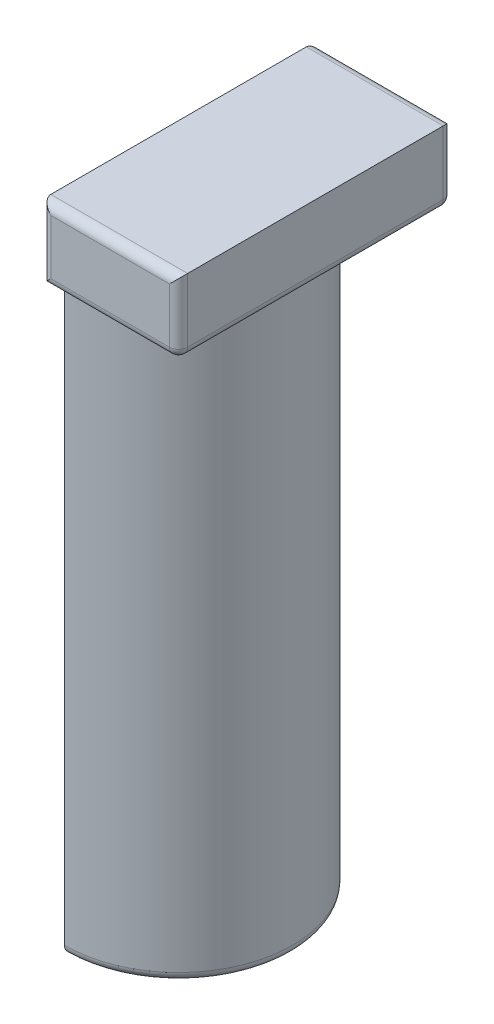
SolidWorks part; units mm, degrees
ref_plane "前视基准面" through (0, 0, 0) normal (0, 0, 1) x (1, 0, 0)
ref_plane "上视基准面" through (0, 0, 0) normal (0, 1, 0) x (1, 0, 0)
ref_plane "右视基准面" through (0, 0, 0) normal (1, 0, 0) x (0, 0, -1)
other "Configuration Table"
sketch "草图1" plane through (0, 0, 0) normal (0, 1, 0) x (1, 0, 0)
  line L1 (0, 0) -> (-30, 0)
  line L2 (0, 0) -> (0, 30)
  line L3 (0, 30) -> (-30, 30)
  line L4 (-30, 0) -> (-30, 30)
  dimension "D1" = 30
  dimension "D2" = 30
extrude "凸台-拉伸1" add sketch "草图1" along normal blind 8
sketch "草图2" plane through (0, 0, 0) normal (0, -1, 0) x (1, 0, 0)
  line L0 (-30, 0) -> (0, 0) construction
  line L1 (-30, -30) -> (-30, 0) construction
  circle A0 centre (-15, -15) radius 12.5
  dimension "D2" = 15
  dimension "D3" = 25
  dimension "D1" = 15
extrude "凸台-拉伸2" add sketch "草图2" along normal blind 65
sketch "草图3" plane through (0, 8, 0) normal (0, 1, 0) x (1, 0, 0)
  line L0 (0, 30) -> (-30, 30) construction
  line L1 (-15, 30) -> (-30, 30)
  line L2 (-15, 30) -> (-15, 0)
  line L3 (-15, 0) -> (-30, 0)
  line L4 (-30, 30) -> (-30, 0)
extrude "切除-拉伸1" cut sketch "草图3" against normal through all
fillet "圆角1" radius 1 1 edges at (-2.5, -65, -15)
fillet "圆角2" radius 1 9 edges at (0, 4, -30) (-7.5, 8, -30) (-15, 4, -30) (-7.5, 0, -30) (0, 4, 0) (-7.5, 0, 0) (-15, 4, 0) (-7.5, 8, 0) (0, 0, -15)
